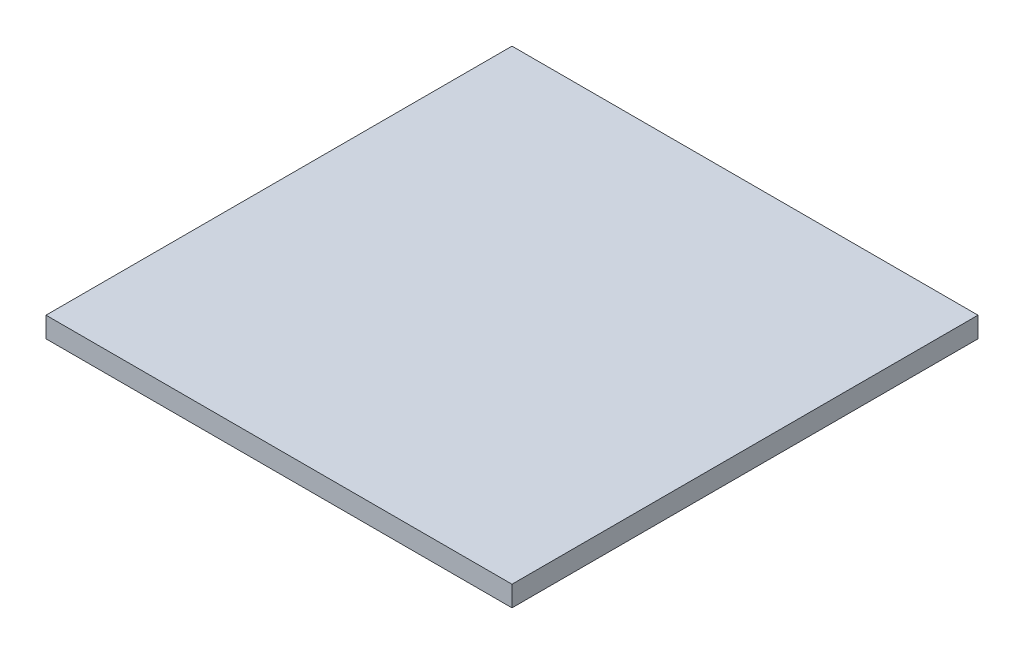
SolidWorks part; units mm, degrees
ref_plane "前视基准面" through (0, 0, 0) normal (0, 0, 1) x (1, 0, 0)
ref_plane "上视基准面" through (0, 0, 0) normal (0, 1, 0) x (1, 0, 0)
ref_plane "右视基准面" through (0, 0, 0) normal (1, 0, 0) x (0, 0, -1)
other "Configuration Table"
sketch "草图1" plane through (0, 0, 0) normal (0, 1, 0) x (1, 0, 0)
  line L1 (0, 0) -> (25, 0)
  line L2 (0, 0) -> (0, 25)
  line L3 (0, 25) -> (25, 25)
  line L4 (25, 0) -> (25, 25)
  line L5 (0, 0) -> (25, 25) construction
  line L6 (0, 25) -> (25, 0) construction
  point P4 (12.5, 12.5)
  dimension "D1" = 25
  dimension "D2" = 25
extrude "凸台-拉伸1" add sketch "草图1" along normal blind 1.1
sketch "草图2" plane through (0, 1.1, 0) normal (0, 1, 0) x (1, 0, 0)
  line L0 (25, 25) -> (0, 25) construction
  line L1 (0, 25) -> (0, 0) construction
  line L2 (25, 0) -> (25, 25) construction
  circle A0 centre (12.5, 12.5) radius 12.5
